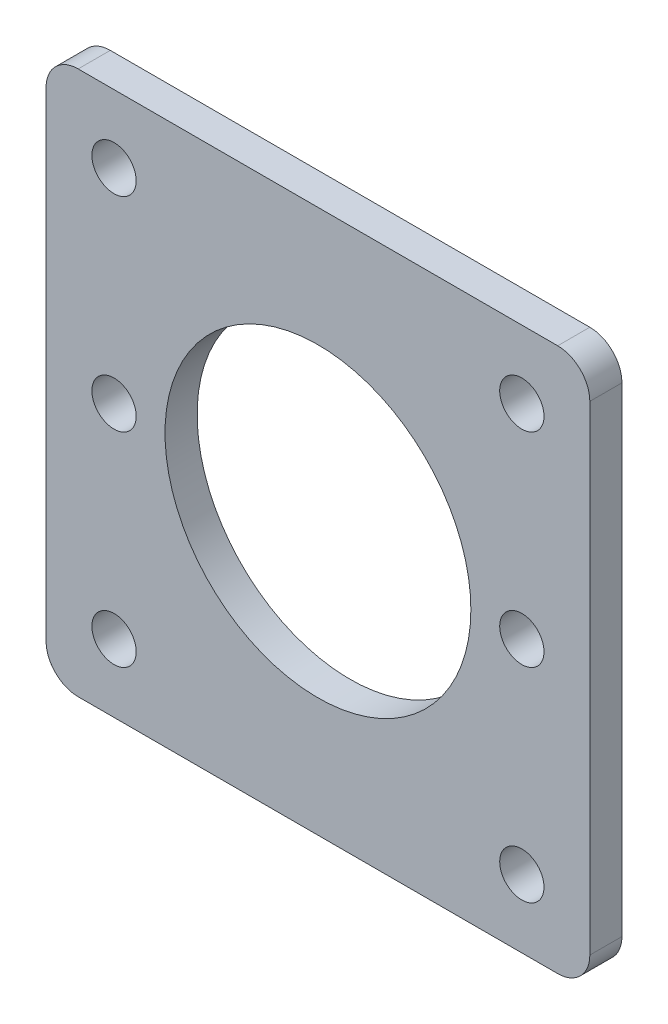
SolidWorks part; units mm, degrees
ref_plane "Front Plane" through (0, 0, 0) normal (0, 0, 1) x (1, 0, 0)
ref_plane "Top Plane" through (0, 0, 0) normal (0, 1, 0) x (1, 0, 0)
ref_plane "Right Plane" through (0, 0, 0) normal (1, 0, 0) x (0, 0, -1)
sketch "Sketch1" plane through (0, 0, 0) normal (0, 0, 1) x (1, 0, 0)
  line L0 (0, 0) -> (-25.4, 0) construction
  line L1 (-25.4, 25.4) -> (25.4, 25.4)
  line L2 (-25.4, 25.4) -> (-25.4, -25.4)
  line L3 (-25.4, -25.4) -> (25.4, -25.4)
  line L4 (25.4, 25.4) -> (25.4, -25.4)
  line L5 (-25.4, 25.4) -> (25.4, -25.4) construction
  line L6 (-25.4, -25.4) -> (25.4, 25.4) construction
  line L7 (0, -55) -> (0, 55) construction
  circle A0 centre (0, 0) radius 14.2875
  circle A1 centre (-19.05, 19.05) radius 2.07
  circle A2 centre (19.05, -19.05) radius 2.07
  circle A3 centre (19.05, 19.05) radius 2.07
  circle A4 centre (-19.05, -19.05) radius 2.07
  circle A5 centre (-19.05, 0) radius 2.07
  circle A6 centre (19.05, 0) radius 2.07
  point P17 (0, 0)
  dimension "D1" = 28.575
  dimension "D3" = 4.14
  dimension "D2" = 50.8
  dimension "D4" = 6.35
  dimension "D5" = 6.35
extrude "Boss-Extrude1" add sketch "Sketch1" along normal mid plane 3
fillet "Fillet1" radius 3 4 edges at (-25.4, -25.4, 0) (25.4, -25.4, 0) (25.4, 25.4, 0) (-25.4, 25.4, 0)
